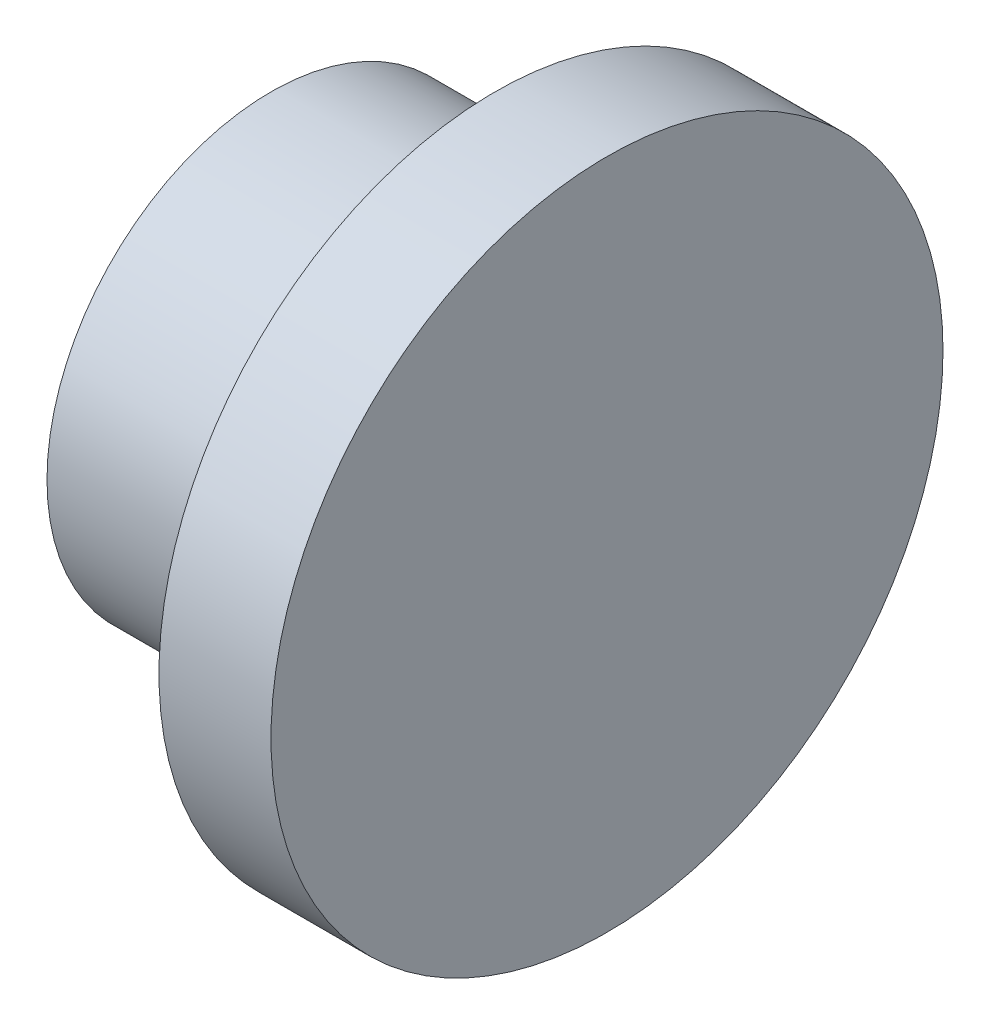
SolidWorks part; units mm, degrees
ref_plane "Front Plane" through (0, 0, 0) normal (0, 0, 1) x (1, 0, 0)
ref_plane "Top Plane" through (0, 0, 0) normal (0, 1, 0) x (1, 0, 0)
ref_plane "Right Plane" through (0, 0, 0) normal (1, 0, 0) x (0, 0, -1)
sketch "Sketch1" plane through (0, 0, 0) normal (1, 0, 0) x (0, 0, -1)
  circle A0 centre (0, 0) radius 15
  dimension "D1" = 30
extrude "Boss-Extrude1" add sketch "Sketch1" along normal blind 5
sketch "Sketch2" plane through (0, 0, 0) normal (-1, 0, 0) x (0, 0, 1)
  circle A0 centre (0, 0) radius 10
  dimension "D1" = 20
extrude "Boss-Extrude2" add sketch "Sketch2" along normal blind 10
sketch "Sketch3" plane through (-10, 0, 0) normal (-1, 0, 0) x (0, 0, 1)
  circle A0 centre (0, 0) radius 5
  dimension "D1" = 10
extrude "Cut-Extrude1" cut sketch "Sketch3" against normal blind 10
